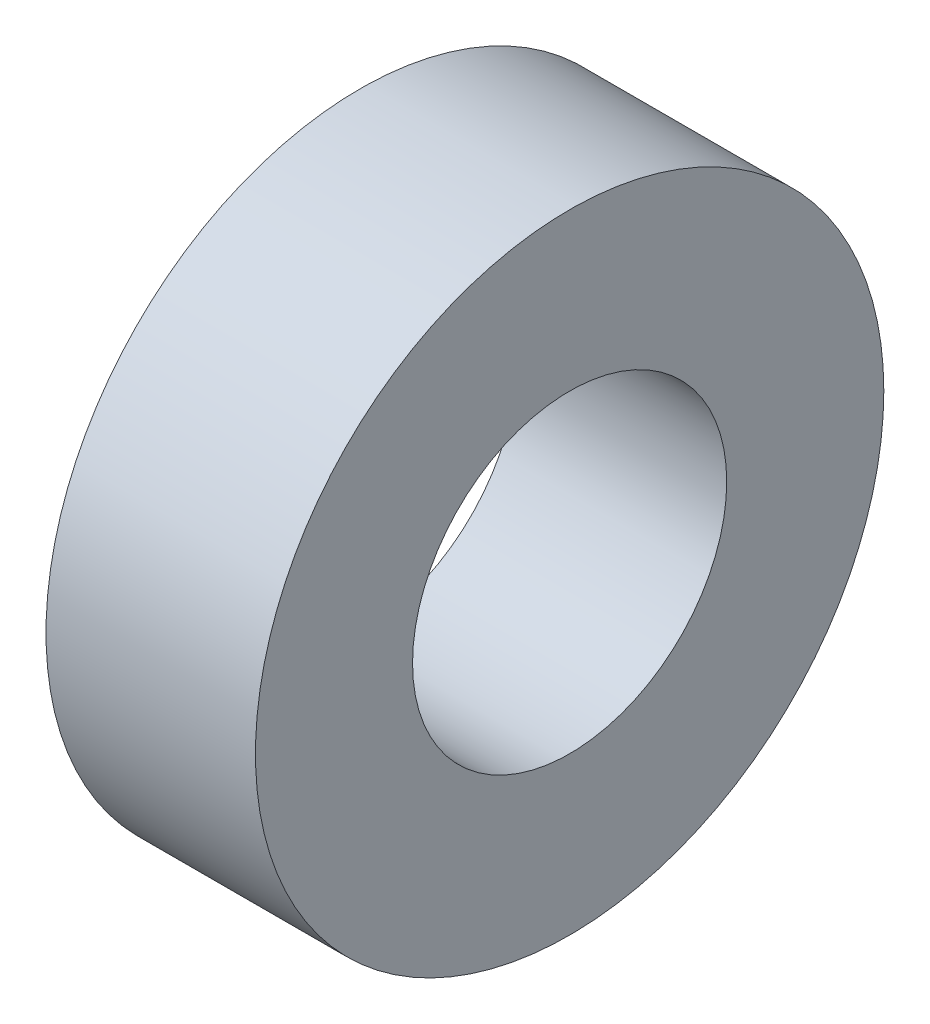
SolidWorks part; units mm, degrees
material "炭素鋼(普通)"
ref_plane "正面" through (0, 0, 0) normal (0, 0, 1) x (1, 0, 0)
ref_plane "平面" through (0, 0, 0) normal (0, 1, 0) x (1, 0, 0)
ref_plane "右側面" through (0, 0, 0) normal (1, 0, 0) x (0, 0, -1)
sketch "ｽｹｯﾁ1" plane through (0, 0, 0) normal (1, 0, 0) x (0, 0, -1)
  circle A0 centre (0, 0) radius 3
  circle A1 centre (0, 0) radius 1.5
  dimension "D1" = 6
  dimension "D2" = 3
extrude "ﾎﾞｽ - 押し出し1" add sketch "ｽｹｯﾁ1" along normal blind 2
